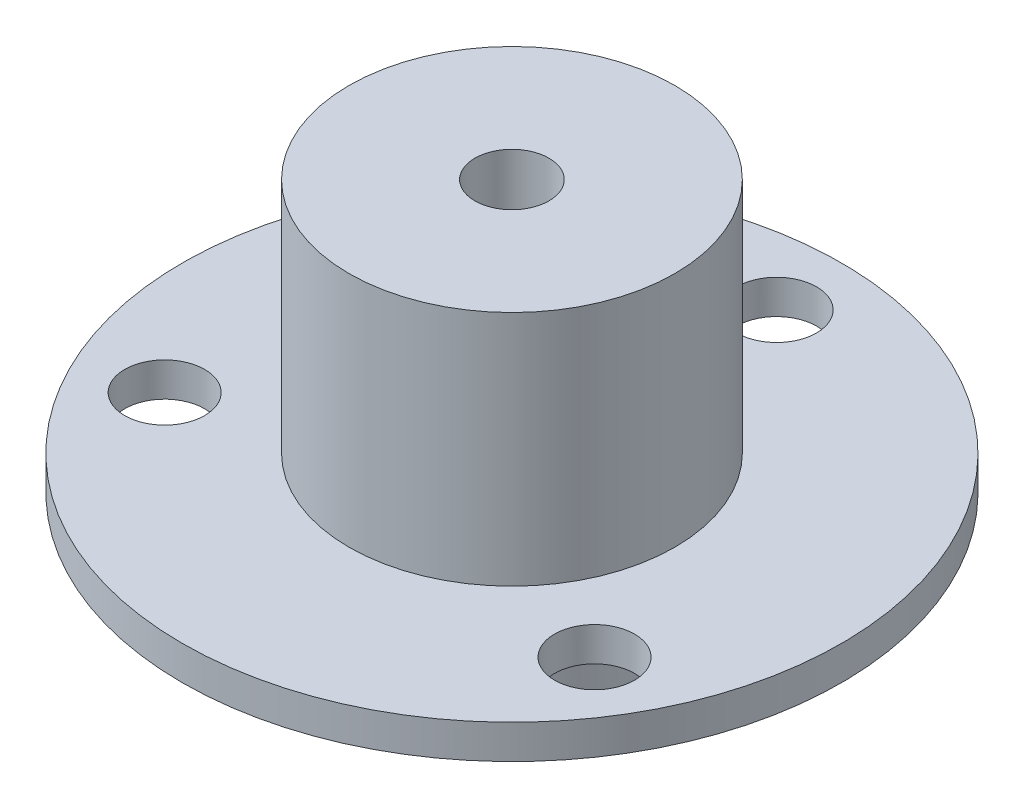
SolidWorks part; units mm, degrees
ref_plane "Front Plane" through (0, 0, 0) normal (0, 0, 1) x (1, 0, 0)
ref_plane "Top Plane" through (0, 0, 0) normal (0, 1, 0) x (1, 0, 0)
ref_plane "Right Plane" through (0, 0, 0) normal (1, 0, 0) x (0, 0, -1)
sketch "Sketch1" plane through (0, 0, 0) normal (0, 1, 0) x (1, 0, 0)
  circle A0 centre (0, 0) radius 11
extrude "Boss-Extrude1" add sketch "Sketch1" along normal blind 5
sketch "Sketch2" plane through (0, 5, 0) normal (0, 1, 0) x (1, 0, 0)
  circle A0 centre (0, 0) radius 22.25
extrude "Boss-Extrude2" add sketch "Sketch2" along normal blind 2.3
sketch "Sketch3" plane through (0, 7.3, 0) normal (0, 1, 0) x (1, 0, 0)
  circle A0 centre (0, 0) radius 11
extrude "Boss-Extrude3" add sketch "Sketch3" along normal blind 16
sketch "Sketch4" plane through (0, 0, 0) normal (0, -1, 0) x (1, 0, 0)
  circle A0 centre (0, 0) radius 2.5
extrude "Cut-Extrude1" cut sketch "Sketch4" against normal blind 30
sketch "Sketch5" plane through (0, 5, 0) normal (0, -1, 0) x (1, 0, 0)
  circle A0 centre (0, 0) radius 17.3205
  circle A1 centre (-15.2702, 8.1744) radius 2.7
  circle A2 centre (14.7143, 9.1372) radius 2.7
  circle A3 centre (0.5559, -17.3116) radius 2.7
  dimension "D1" = 5.4
  dimension "D2" = 5.4
  dimension "D3" = 5.4
  dimension "D4" = 30
  dimension "D5" = 30
  dimension "D6" = 30
extrude "Cut-Extrude2" cut sketch "Sketch5" against normal blind 16 contours A0 A1 | A0 A1 | A0 A3 | A0 A3 | A0 A2 | A0 A2
